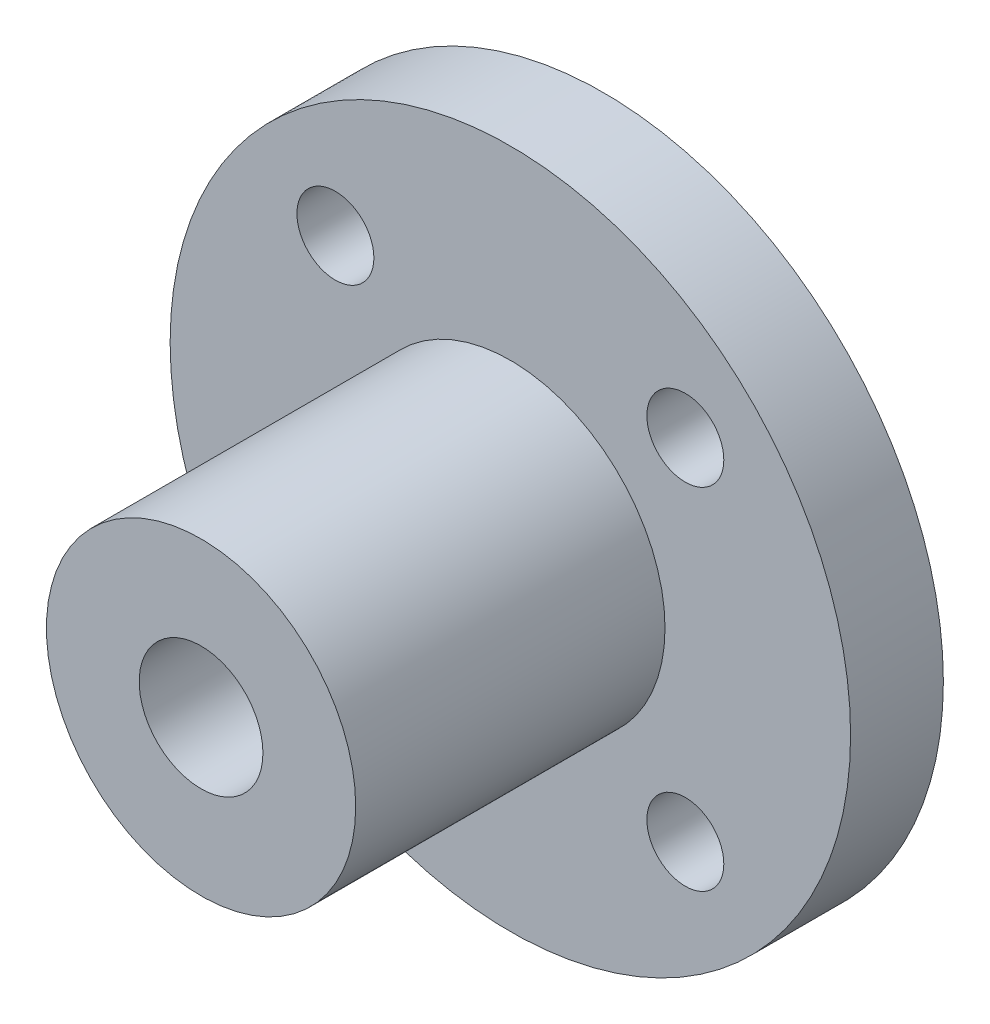
SolidWorks part; units mm, degrees
ref_plane "Front Plane" through (0, 0, 0) normal (0, 0, 1) x (1, 0, 0)
ref_plane "Top Plane" through (0, 0, 0) normal (0, 1, 0) x (1, 0, 0)
ref_plane "Right Plane" through (0, 0, 0) normal (1, 0, 0) x (0, 0, -1)
sketch "Sketch2" plane through (0, 0, 0) normal (0, 0, 1) x (1, 0, 0)
  line L1 (-5.6569, -5.6569) -> (5.6569, -5.6569) construction
  line L2 (-5.6569, -5.6569) -> (-5.6569, 5.6569) construction
  line L3 (-5.6569, 5.6569) -> (5.6569, 5.6569) construction
  line L4 (5.6569, -5.6569) -> (5.6569, 5.6569) construction
  line L5 (-5.6569, -5.6569) -> (5.6569, 5.6569) construction
  line L6 (-5.6569, 5.6569) -> (5.6569, -5.6569) construction
  circle A0 centre (0, 0) radius 11
  circle A1 centre (0, 0) radius 2
  circle A10 centre (-5.6569, 5.6569) radius 1.2442
  circle A11 centre (5.6569, 5.6569) radius 1.2442
  circle A12 centre (5.6569, -5.6569) radius 1.2442
  circle A13 centre (-5.6569, -5.6569) radius 1.2442
  point P15 (0, 0)
  dimension "D1" = 16
  dimension "D2" = 22
  dimension "D3" = 4
  dimension "D4" = 2.4883
extrude "Boss-Extrude1" add sketch "Sketch2" along normal blind 3
sketch "Sketch3" plane through (0, 0, 3) normal (0, 0, 1) x (1, 0, 0)
  circle A0 centre (0, 0) radius 5
  circle A2 centre (0, 0) radius 2
  dimension "D1" = 10
  dimension "D2" = 4
extrude "Boss-Extrude3" add sketch "Sketch3" along normal blind 10
sketch "Sketch6" plane through (0, 0, 0) normal (0, 1, 0) x (1, 0, 0)
  line L3 (-5, -3) -> (5, -3) construction
  circle A0 centre (0, -8) radius 1.5
  dimension "D1" = 3
  dimension "D2" = 5
extrude "Cut-Extrude2" cut sketch "Sketch6" against normal up to surface (5 mm away)
